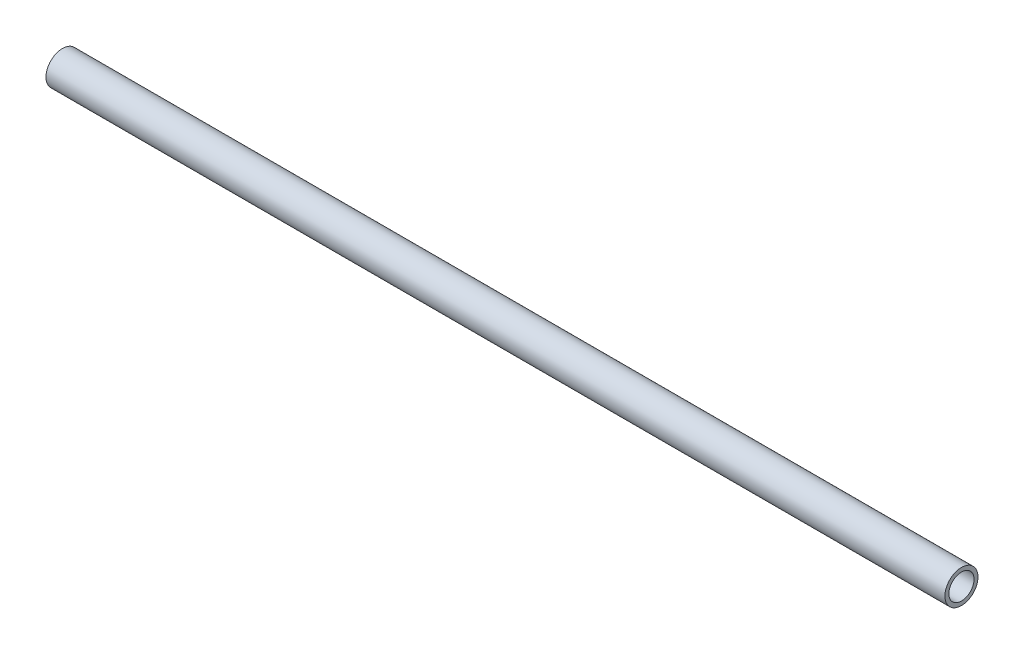
SolidWorks part; units mm, degrees
material "AISI 4130 Steel, annealed at 865C"
ref_plane "Front Plane" through (0, 0, 0) normal (0, 0, 1) x (1, 0, 0)
ref_plane "Top Plane" through (0, 0, 0) normal (0, 1, 0) x (1, 0, 0)
ref_plane "Right Plane" through (0, 0, 0) normal (1, 0, 0) x (0, 0, -1)
sketch "Sketch1" plane through (0, 0, 0) normal (1, 0, 0) x (0, 0, -1)
  circle A0 centre (0, 0) radius 12.7
  circle A1 centre (0, 0) radius 9.652
  dimension "D1" = 25.4
  dimension "D2" = 19.304
extrude "Boss-Extrude1" add sketch "Sketch1" along normal blind 690
